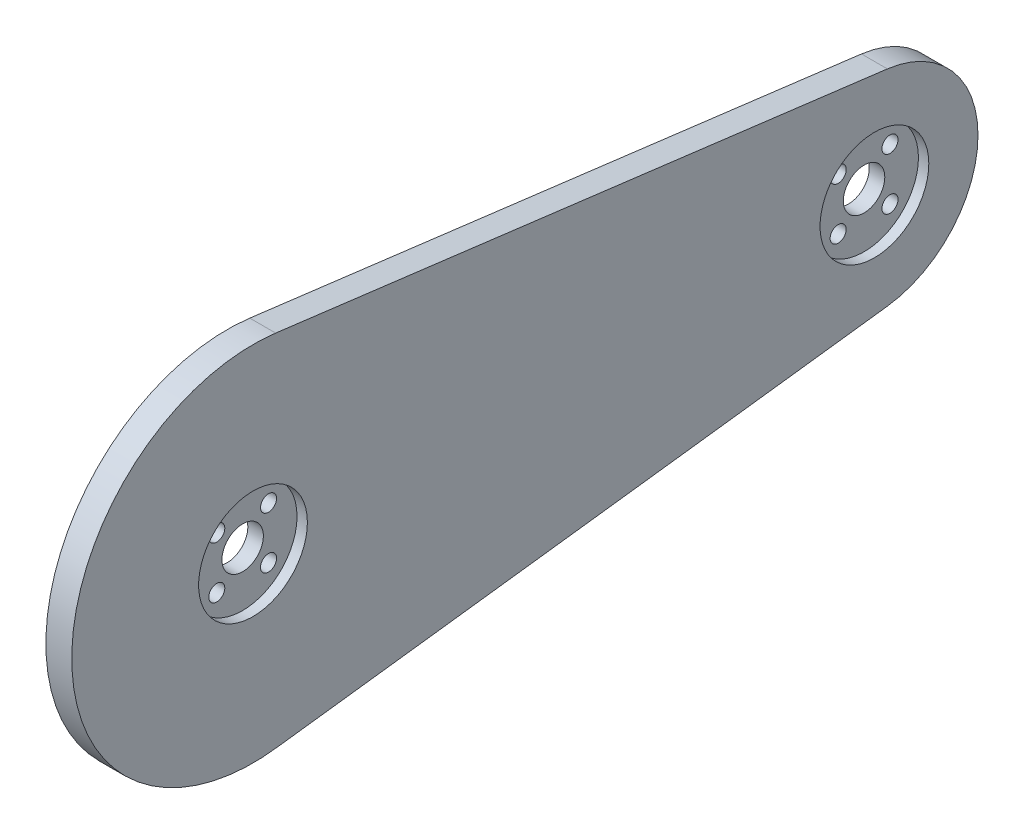
SolidWorks part; units mm, degrees
ref_plane "前视基准面" through (0, 0, 0) normal (0, 0, 1) x (1, 0, 0)
ref_plane "上视基准面" through (0, 0, 0) normal (0, 1, 0) x (1, 0, 0)
ref_plane "右视基准面" through (0, 0, 0) normal (1, 0, 0) x (0, 0, -1)
other "Configuration Table"
sketch "草图1" plane through (0, 0, 0) normal (1, 0, 0) x (0, 0, -1)
  line L0 (0, 0) -> (120, 0)
  line L1 (4.375, 34.7255) -> (122.5, 19.8431)
  line L2 (-5, -5) -> (5, -5)
  line L3 (-5, -5) -> (-5, 5)
  line L4 (-5, 5) -> (5, 5)
  line L5 (5, -5) -> (5, 5)
  line L6 (-5, -5) -> (5, 5) construction
  line L7 (-5, 5) -> (5, -5) construction
  line L8 (115, -5) -> (125, -5)
  line L9 (115, -5) -> (115, 5)
  line L10 (115, 5) -> (125, 5)
  line L11 (125, -5) -> (125, 5)
  line L12 (115, -5) -> (125, 5) construction
  line L13 (115, 5) -> (125, -5) construction
  line L14 (5, -34.641) -> (122.499, -19.8433)
  circle A0 centre (0, 0) radius 35
  circle A1 centre (120, 0) radius 20
  circle A2 centre (0, 0) radius 4
  circle A3 centre (-5, 5) radius 1.55
  circle A4 centre (5, 5) radius 1.55
  circle A5 centre (5, -5) radius 1.55
  circle A6 centre (-5, -5) radius 1.55
  circle A7 centre (120, 0) radius 4
  circle A8 centre (115, 5) radius 1.55
  circle A9 centre (125, 5) radius 1.55
  circle A10 centre (125, -5) radius 1.55
  circle A11 centre (115, -5) radius 1.55
  point P20 (0, 0)
  dimension "D1" = 70
  dimension "D3" = 40
  dimension "D4" = 8
  dimension "D7" = 3.1
  dimension "D9" = 8
  dimension "D12" = 3.1
  dimension "D2" = 120
  dimension "D5" = 10
  dimension "D6" = 10
  dimension "D10" = 10
  dimension "D11" = 10
  dimension "D8" = 4
  dimension "D13" = 4
extrude "凸台-拉伸3" add sketch "草图1" along normal blind 5
sketch "草图3" plane through (5, 0, 0) normal (1, 0, 0) x (0, 0, -1)
  circle A0 centre (0, 0) radius 10.5
  circle A1 centre (120, 0) radius 10.5
  dimension "D1" = 21
  dimension "D2" = 21
extrude "切除-拉伸2" cut sketch "草图3" against normal blind 2
